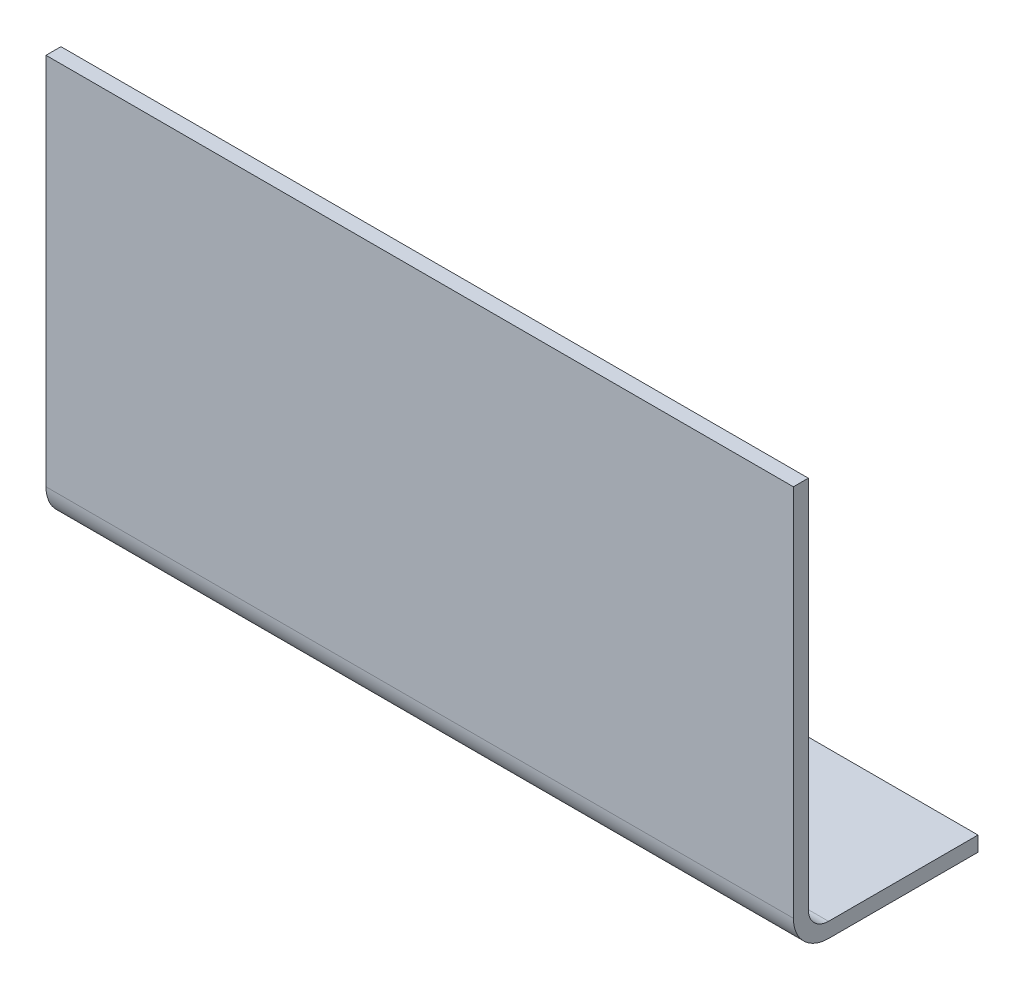
SolidWorks part; units mm, degrees
ref_plane "Front Plane" through (0, 0, 0) normal (0, 0, 1) x (1, 0, 0)
ref_plane "Top Plane" through (0, 0, 0) normal (0, 1, 0) x (1, 0, 0)
ref_plane "Right Plane" through (0, 0, 0) normal (1, 0, 0) x (0, 0, -1)
sketch "Sketch1" plane through (0, 0, 0) normal (1, 0, 0) x (0, 0, -1)
  line L0 (0, 41.9244) -> (0, -41.9244) construction
  line L1 (-4, 3.7465) -> (-4, -46.2535)
  line L2 (0.7, -50.9535) -> (20.7, -50.9535)
  line L3 (20.7, -50.9535) -> (20.7, -48.9535)
  line L4 (20.7, -48.9535) -> (0.7, -48.9535)
  line L5 (-2, -46.2535) -> (-2, 3.7465)
  line L6 (-2, 3.7465) -> (-4, 3.7465)
  arc A0 (-4, -46.2535) -> (0.7, -50.9535) centre (0.7, -46.2535) ccw
  arc A1 (0.7, -48.9535) -> (-2, -46.2535) centre (0.7, -46.2535) cw
  dimension "D3" = 2.7
  dimension "D4" = 4.7
  dimension "D1" = 4
  dimension "D2" = 8
  dimension "D5" = 2
  dimension "D6" = 50
  dimension "D7" = 20
extrude "Boss-Extrude1" add sketch "Sketch1" along normal mid plane 100
